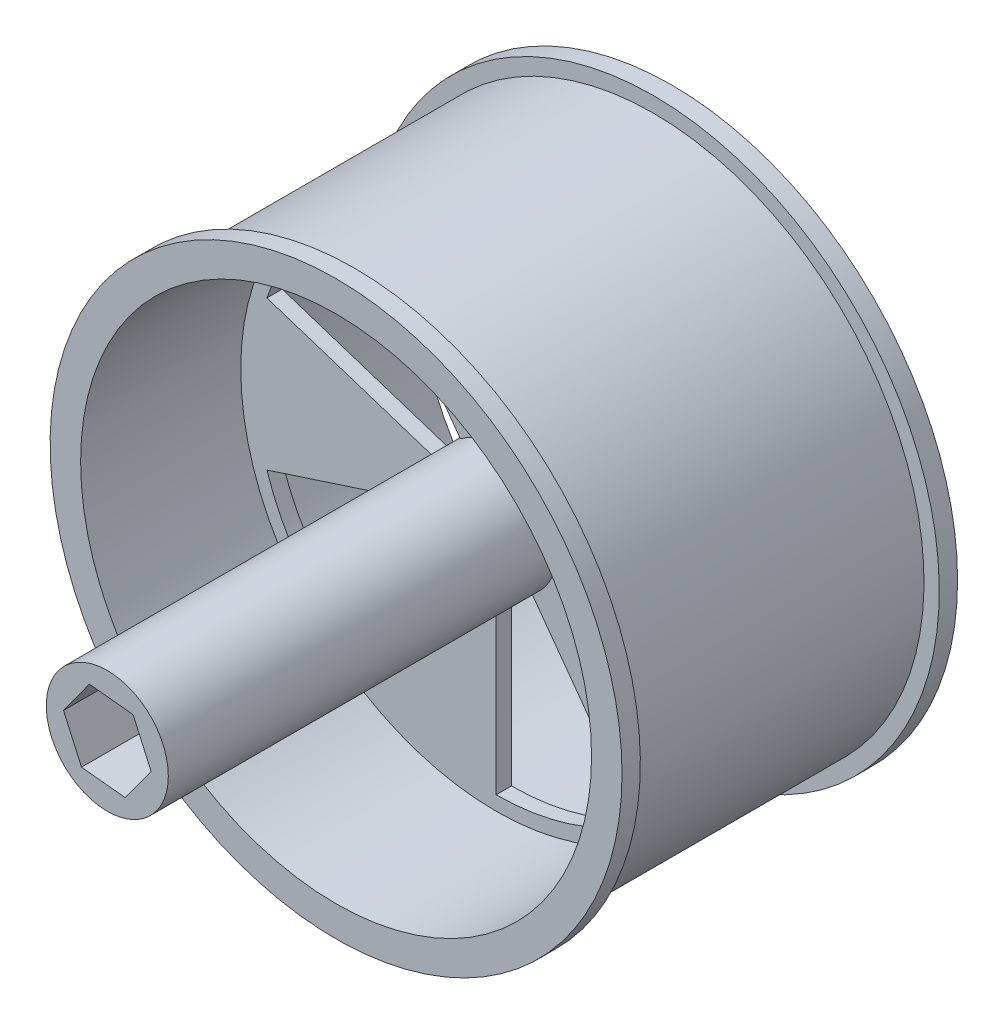
SolidWorks part; units mm, degrees
ref_plane "Front" through (0, 0, 0) normal (0, 0, 1) x (1, 0, 0)
ref_plane "Top" through (0, 0, 0) normal (0, 1, 0) x (1, 0, 0)
ref_plane "Right" through (0, 0, 0) normal (1, 0, 0) x (0, 0, -1)
sketch "Sketch1" plane through (0, 0, 0) normal (0, 0, 1) x (1, 0, 0)
  circle A0 centre (0, 0) radius 23.8125
  circle A1 centre (0, 0) radius 21.2725
  dimension "D1" = 47.625
  dimension "D2" = 2.54
extrude "Boss-Extrude1" add sketch "Sketch1" along normal blind 27.94
sketch "Sketch2" plane through (0, 0, 0) normal (1, 0, 0) x (0, 0, -1)
  line L1 (-1.524, 23.8125) -> (-26.416, 23.8125)
  line L2 (-1.524, 23.8125) -> (-1.524, 22.5425)
  line L3 (-1.524, 22.5425) -> (-26.416, 22.5425)
  line L4 (-26.416, 23.8125) -> (-26.416, 22.5425)
  line L5 (0, 0) -> (-26.416, 0) construction
  line L7 (-27.94, 23.8125) -> (-27.94, -23.8125) construction
  line L8 (0, -23.8125) -> (0, 23.8125) construction
  line L9 (-26.416, 23.8125) -> (-27.94, 23.8125) construction
  point P4 (0, 0)
  point P5 (-27.94, 26.1093)
  point P6 (-27.94, 25.337)
  dimension "D1" = 1.27
  dimension "D2" = 1.524
  dimension "D3" = 1.524
  dimension "D4" = 23.8125
revolve "Cut-Revolve2" cut sketch "Sketch2" angle 360 about L5
ref_plane "Plane2" through (0, 0, 13.97) normal (0, 0, 1) x (1, 0, 0)
sketch "Sketch5" plane through (0, 0, 13.97) normal (0, 0, 1) x (1, 0, 0)
  circle A0 centre (0, 0) radius 21.2725
  dimension "D1" = 42.545
extrude "Boss-Extrude2" add sketch "Sketch5" along normal mid plane 1.27
sketch "Sketch6" plane through (0, 0, 14.605) normal (0, 0, 1) x (1, 0, 0)
  line L0 (0, 5.08) -> (0, 20.0763)
  line L1 (2.9859, 4.1098) -> (11.8005, 16.2421)
  line L2 (4.8314, 1.5698) -> (19.0937, 6.2039)
  line L3 (4.8314, -1.5698) -> (19.0937, -6.2039)
  line L4 (2.9859, -4.1098) -> (11.8005, -16.2421)
  line L5 (0, -5.08) -> (0, -20.0763)
  line L6 (-2.9859, -4.1098) -> (-11.8005, -16.2421)
  line L7 (-4.8314, -1.5698) -> (-19.0937, -6.2039)
  line L8 (-4.8314, 1.5698) -> (-19.0937, 6.2039)
  line L9 (-2.9859, 4.1098) -> (-11.8005, 16.2421)
  arc A0 (-2.9859, 4.1098) -> (-4.8314, 1.5698) centre (0, 0) ccw
  arc A1 (19.0937, 6.2039) -> (19.0937, -6.2039) centre (0, 0) cw
  arc A2 (0, 20.0763) -> (11.8005, 16.2421) centre (0, 0) cw
  arc A3 (11.8005, -16.2421) -> (0, -20.0763) centre (0, 0) cw
  arc A4 (-11.8005, -16.2421) -> (-19.0937, -6.2039) centre (0, 0) cw
  arc A5 (-19.0937, 6.2039) -> (-11.8005, 16.2421) centre (0, 0) cw
  arc A6 (2.9859, 4.1098) -> (0, 5.08) centre (0, 0) ccw
  arc A7 (4.8314, -1.5698) -> (4.8314, 1.5698) centre (0, 0) ccw
  arc A8 (0, -5.08) -> (2.9859, -4.1098) centre (0, 0) ccw
  arc A9 (-4.8314, -1.5698) -> (-2.9859, -4.1098) centre (0, 0) ccw
  point P27 (0, 0)
  dimension "D1" = 36
  dimension "D2" = 5
  dimension "D3" = 10.16
extrude "Cut-Extrude2" cut sketch "Sketch6" against normal through all both and the other way through all
sketch "Sketch7" plane through (0, 0, 14.605) normal (0, 0, 1) x (1, 0, 0)
  circle A0 centre (0, 0) radius 5.08
  dimension "D1" = 10.16
extrude "Boss-Extrude7" add sketch "Sketch7" along normal offset from surface (32.385 mm away) 19.05 up to face at (23.8125, 0, 27.94) offset beyond the face yes
sketch "Sketch8" plane through (0, 0, 46.99) normal (0, 0, 1) x (1, 0, 0)
  line L1 (-1.4983, 3.346) -> (-3.6469, 0.3755)
  line L2 (-3.6469, 0.3755) -> (-2.1486, -2.9706)
  line L3 (-2.1486, -2.9706) -> (1.4983, -3.346)
  line L4 (1.4983, -3.346) -> (3.6469, -0.3755)
  line L5 (3.6469, -0.3755) -> (2.1486, 2.9706)
  line L6 (2.1486, 2.9706) -> (-1.4983, 3.346)
  circle A0 centre (0, 0) radius 3.175 construction
  dimension "D1" = 6.35
extrude "Cut-Extrude3" cut sketch "Sketch8" against normal blind 19.05
equation "\"D3@Sketch2\"=\"D2@Sketch2\""
